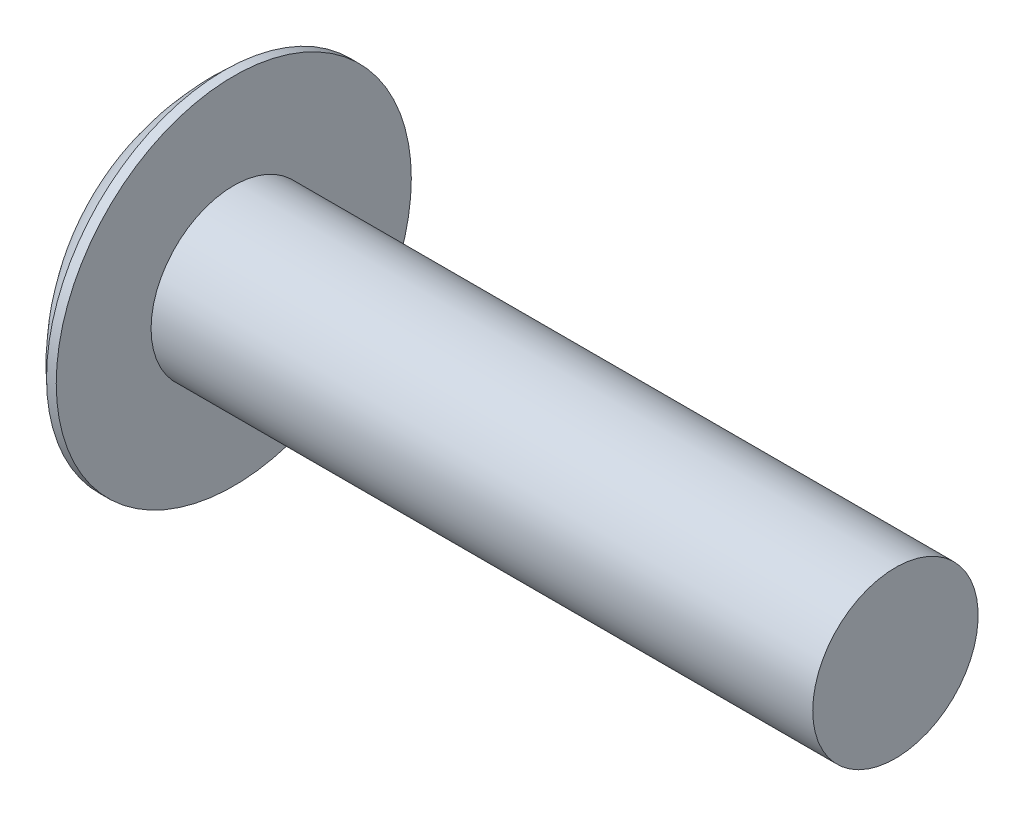
SolidWorks part; units mm, degrees
ref_plane "Plane1" through (0, 0, 0) normal (0, 0, 1) x (1, 0, 0)
ref_plane "Plane2" through (0, 0, 0) normal (0, 1, 0) x (1, 0, 0)
ref_plane "Plane3" through (0, 0, 0) normal (1, 0, 0) x (0, 0, -1)
sketch "BodySke" plane through (0, 0, 0) normal (0, 0, 1) x (1, 0, 0)
  line L0 (5.1562, 4.7625) -> (5.1562, 10.2235)
  line L1 (43.2562, 0) -> (0, 0)
  line L2 (-25.4, 0) -> (127, 0) construction
  line L3 (4.5978, -10.2235) -> (5.1562, -10.2235) construction
  line L4 (5.1562, 4.7625) -> (43.2562, 4.7625)
  line L5 (43.2562, 4.7625) -> (43.2562, 0)
  line L6 (4.5978, 10.2235) -> (5.1562, 10.2235)
  line L7 (5.1562, -4.7625) -> (43.2562, -4.7625) construction
  line L8 (6.7437, 6.35) -> (6.7437, -3.175) construction
  line L9 (11.5062, 6.35) -> (11.5062, -3.175) construction
  arc A0 (4.5978, 10.2235) -> (0, 0) centre (13.6652, 0) ccw
  dimension "Head_rad" = 13.6652
  dimension "Diameter" = 9.525
  dimension "Length" = 38.1
  dimension "Head_ht" = 5.1562
  dimension "Head_dia" = 20.447
  dimension "Advance" = 1.5875
  dimension "Thread_nom" = 31.75
revolve "Base-Revolve" add sketch "BodySke" angle 360 about L2
cosmetic thread "ThreadCosmetic" [suppressed] parameters "Thread_length"=31.75, "Thread_minor"=7.9375
sketch "Sketch2" plane through (0, 0, 0) normal (1, 0, 0) x (0, 0, -1)
  line L0 (10.2235, -1.1049) -> (-10.2235, -1.1049)
  line L1 (10.2235, -1.1049) -> (10.2235, 1.1049)
  line L2 (-10.2235, 1.1049) -> (10.2235, 1.1049)
  line L3 (-10.2235, 1.1049) -> (-10.2235, -1.1049)
  dimension "D1" = 20.447
  dimension "Slot_width" = 2.2098
  dimension "D2" = 10.2235
  dimension "D3" = 1.1049
extrude "Slot" cut sketch "Sketch2" along normal blind 2.8448
sketch "Sketch3" plane through (0, 0, 0) normal (1, 0, 0) x (0, 0, -1)
  line L0 (1.2319, -7.4676) -> (-1.2319, -7.4676)
  line L1 (1.2319, -7.4676) -> (1.2319, 7.4676)
  line L2 (-1.2319, 7.4676) -> (1.2319, 7.4676)
  line L3 (-1.2319, 7.4676) -> (-1.2319, -7.4676)
  dimension "Cross_width" = 2.4638
  dimension "Cross_dia" = 14.9352
  dimension "D1" = 1.2319
  dimension "D2" = 7.4676
ref_plane "Plane4" through (8.9916, 0, 0) normal (1, 0, 0) x (0, 0, -1)
sketch "Sketch4" plane through (8.9916, 0, 0) normal (1, 0, 0) x (0, 0, -1)
  line L0 (0.616, -0.616) -> (-0.616, -0.6159)
  line L1 (0.616, -0.616) -> (0.616, 0.616)
  line L2 (-0.616, 0.616) -> (0.616, 0.616)
  line L3 (-0.616, 0.616) -> (-0.616, -0.6159)
  dimension "D1" = 1.2319
  dimension "D2" = 0.6159
  dimension "D3" = 1.2319
  dimension "D4" = 0.6159
loft "Cross" cut profiles "Sketch3", "Sketch4"
pattern_circular "CirPattern1" count 2 every 90 about axis through (0, 0, 0) along (1, 0, 0) of "Cross"
sketch "ThdSchSke" plane through (0, 0, 0) normal (0, 0, 1) x (1, 0, 0)
  line L0 (11.5062, -3.9688) -> (10.9504, -4.7625)
  line L1 (11.5062, -3.9688) -> (12.062, -4.7625)
  line L2 (12.062, -4.7625) -> (12.062, -5.9531)
  line L3 (-3.175, 0) -> (5.1513, 0) construction
  line L5 (12.062, -5.9531) -> (10.9504, -5.9531)
  line L6 (10.9504, -5.9531) -> (10.9504, -4.7625)
  dimension "Diameter" = 9.525
  dimension "SideAngle" = 55
  dimension "VeeAngle" = 70
  dimension "Thread_minor" = 7.9375
  dimension "Overcut" = 11.9063
  dimension "Start" = 11.5062
revolve "ThreadSchematic" [suppressed] cut sketch "ThdSchSke" angle 360 about L3
pattern_linear "ThdSchPat" [suppressed]
equation "\"D1@Sketch2\" = \"Head_dia@BodySke\""
equation "\"D2@Sketch2\" = \"D1@Sketch2\" / 2"
equation "\"D3@Sketch2\" = \"Slot_width@Sketch2\" / 2"
equation "\"D1@Sketch3\" = \"Cross_width@Sketch3\" / 2"
equation "\"D2@Sketch3\" = \"Cross_dia@Sketch3\" / 2"
equation "\"D1@Sketch4\" = \"Cross_width@Sketch3\" *.5"
equation "\"D2@Sketch4\" = \"D1@Sketch4\" / 2"
equation "\"D3@Sketch4\" = \"D1@Sketch4\""
equation "\"D4@Sketch4\" = \"D3@Sketch4\" / 2"
equation "\"Thread_length@ThreadCosmetic\" = ((sgn( (\"Length@BodySke\" - \"Advance@BodySke\" ) - \"Thread_nom@BodySke\" )-1)*( (\"Length@BodySke\" - \"Advance@BodySke\" ) - \"Thread_nom@BodySke\" ))/-2+ \"Thread_nom@BodySke\""
equation "\"Thread_minor@ThdSchSke\" = \"Thread_minor@ThreadCosmetic\""
equation "\"Diameter@ThdSchSke\" = \"Diameter@BodySke\""
equation "\"Overcut@ThdSchSke\" = \"Diameter@BodySke\" * 1.25"
equation "\"Start@ThdSchSke\" = \"Head_ht@BodySke\" + \"Length@BodySke\" - \"Thread_length@ThreadCosmetic\"  '---Non-countersunk---"
equation "\"Num_threads@ThdSchPat\" = int( \"Thread_length@ThreadCosmetic\" / \"Advance@BodySke\" + 0.999 )  + 1"
equation "\"Advance@ThdSchPat\" = \"Thread_length@ThreadCosmetic\" /  (\"Num_threads@ThdSchPat\" - 1) 'relax it"
